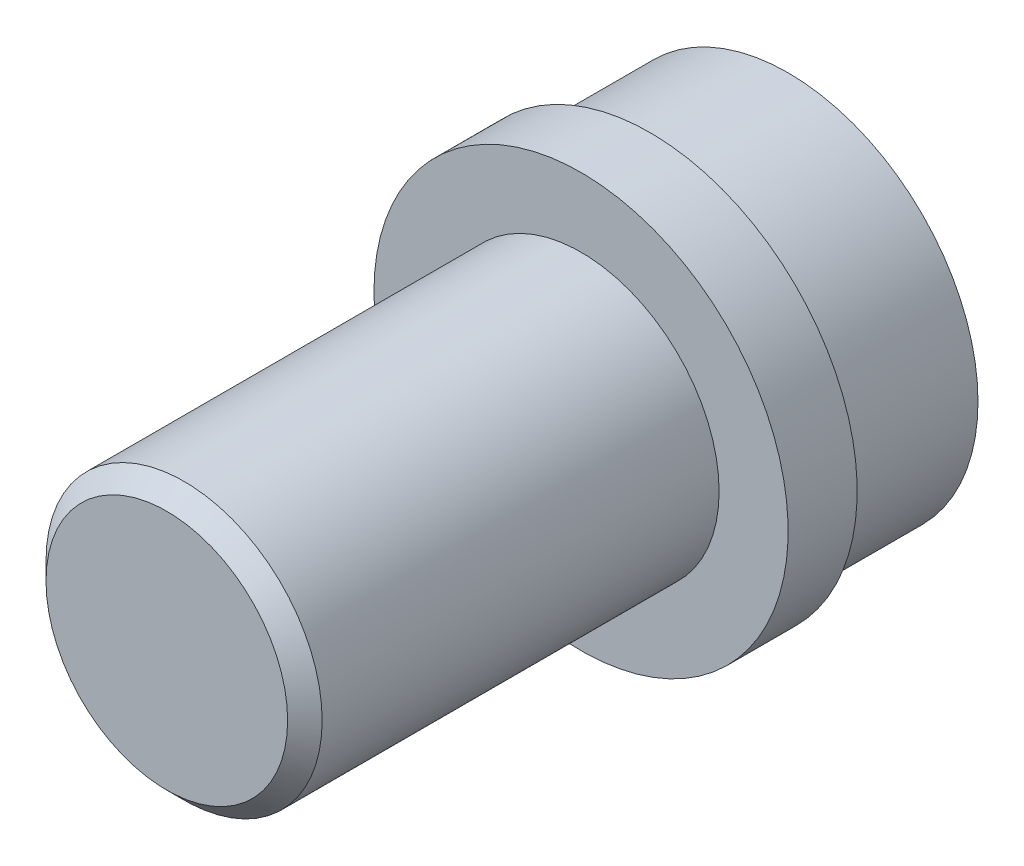
SolidWorks part; units mm, degrees
ref_plane "前视基准面" through (0, 0, 0) normal (0, 0, 1) x (1, 0, 0)
ref_plane "上视基准面" through (0, 0, 0) normal (0, 1, 0) x (1, 0, 0)
ref_plane "右视基准面" through (0, 0, 0) normal (1, 0, 0) x (0, 0, -1)
sketch "草图1" plane through (0, 0, 0) normal (0, 0, 1) x (1, 0, 0)
  circle A0 centre (0, 0) radius 4
extrude "凸台-拉伸1" add sketch "草图1" along normal blind 12
cosmetic thread "装饰螺纹线1" parameters "D1"=5, "D2"=7
sketch "草图2" plane through (0, 0, 0) normal (0, 0, -1) x (-1, 0, 0)
  circle A0 centre (0, 0) radius 6
extrude "凸台-拉伸2" add sketch "草图2" along normal blind 2
sketch "草图3" plane through (0, 0, -2) normal (0, 0, -1) x (-1, 0, 0)
  circle A0 centre (0, 0) radius 5.5
extrude "凸台-拉伸3" add sketch "草图3" along normal blind 4
sketch "草图4" plane through (0, 0, 0) normal (0, 1, 0) x (1, 0, 0)
  line L0 (0, 9.4057) -> (0, 0) construction
  line L1 (5.5, 6) -> (-5.5, 6) construction
  line L2 (0, 8.2) -> (0, 0.2)
  arc A0 (0, 0.2) -> (0, 8.2) centre (0, 4.2) ccw
  dimension "D1" = 8
  dimension "D2" = 1.8
revolve "旋转1" add sketch "草图4" angle 360 about L0
chamfer "倒角1" distance 0.5 angle 45 1 edges at (4, 0, 12)
